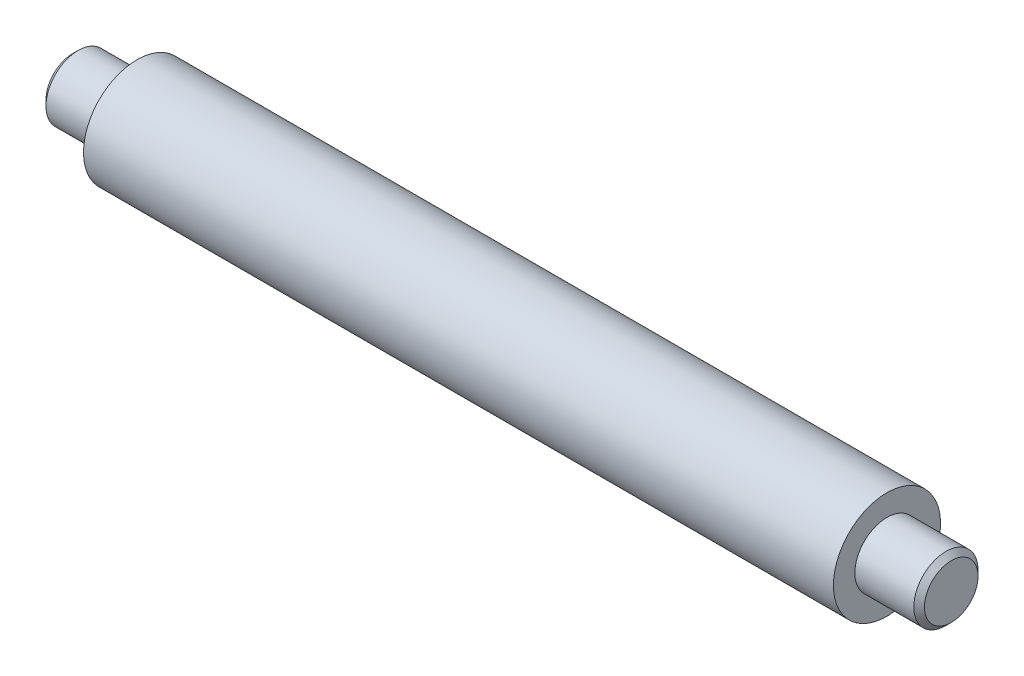
SolidWorks part; units mm, degrees
ref_plane "Front Plane" through (0, 0, 0) normal (0, 0, 1) x (1, 0, 0)
ref_plane "Top Plane" through (0, 0, 0) normal (0, 1, 0) x (1, 0, 0)
ref_plane "Right Plane" through (0, 0, 0) normal (1, 0, 0) x (0, 0, -1)
sketch "Sketch1" plane through (0, 0, 0) normal (0, 0, 1) x (1, 0, 0)
  line L0 (-39.7758, 0) -> (43.35, 0) construction
  line L1 (-20.5, 0) -> (-20.5, 1.5)
  line L2 (-20.5, 1.5) -> (-17.5, 1.5)
  line L3 (-17.5, 1.5) -> (-17.5, 2.5)
  line L4 (-17.5, 2.5) -> (17.5, 2.5)
  line L5 (17.5, 2.5) -> (17.5, 1.5)
  line L6 (17.5, 1.5) -> (20.5, 1.5)
  line L7 (20.5, 1.5) -> (20.5, 0)
  line L8 (20.5, 0) -> (-20.5, 0)
  point P7 (0, 2.5)
  point P12 (30.9842, 0)
  point P13 (-39.7758, 0)
  point P14 (43.35, 0)
  dimension "D1" = 3
  dimension "D2" = 35
  dimension "D3" = 3
  dimension "D4" = 5
revolve "Revolve1" add sketch "Sketch1" angle 360 about L0
cosmetic thread "Cosmetic Thread2" parameters "D2"=2.439
cosmetic thread "Cosmetic Thread3" parameters "D2"=2.439
chamfer "Chamfer2" distance 0.25 angle 45 2 edges at (-20.5, 0, 1.5) (20.5, 0, 1.5)
